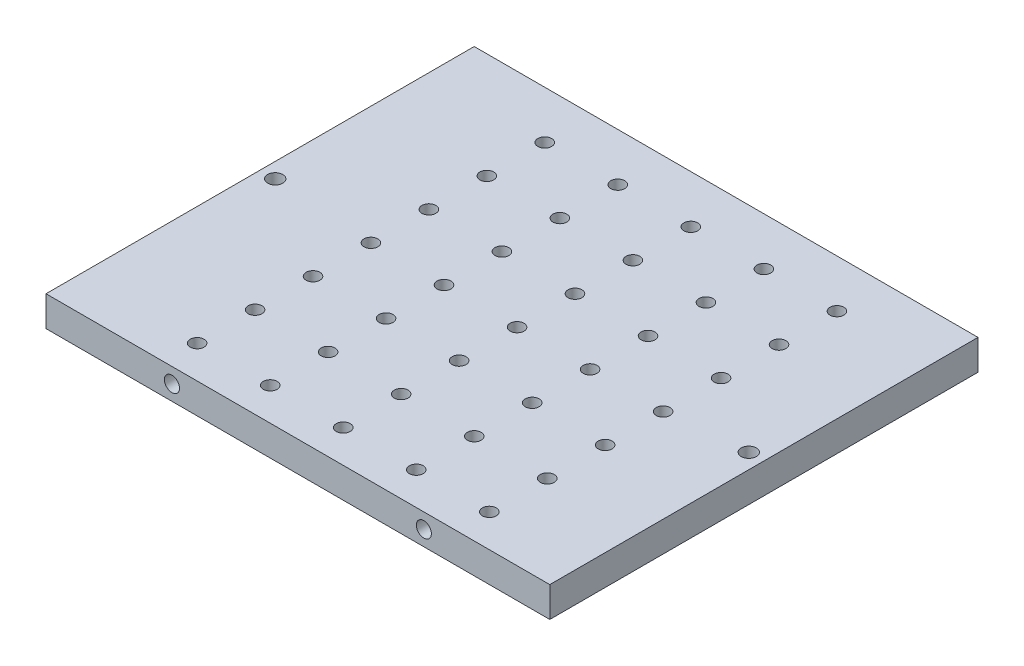
SolidWorks part; units mm, degrees
ref_plane "Plan de face" through (0, 0, 0) normal (0, 0, 1) x (1, 0, 0)
ref_plane "Plan de dessus" through (0, 0, 0) normal (0, 1, 0) x (1, 0, 0)
ref_plane "Plan de droite" through (0, 0, 0) normal (1, 0, 0) x (0, 0, -1)
sketch "Esquisse1" plane through (0, 0, 0) normal (0, 1, 0) x (1, 0, 0)
  line L1 (-50, -42.5) -> (50, -42.5)
  line L2 (-50, -42.5) -> (-50, 42.5)
  line L3 (-50, 42.5) -> (50, 42.5)
  line L4 (50, -42.5) -> (50, 42.5)
  line L5 (-50, -42.5) -> (50, 42.5) construction
  line L6 (-50, 42.5) -> (50, -42.5) construction
  point P0 (0, 0)
  dimension "D1" = 85
  dimension "D2" = 100
extrude "Boss.-Extru.1" add sketch "Esquisse1" along normal blind 6
sketch "Esquisse2" plane through (0, 0, 42.5) normal (0, 0, 1) x (1, 0, 0)
  line L0 (-50, 3) -> (29.6548, 3) construction
  line L3 (-50, 6) -> (-50, 0) construction
  line L5 (0, 0) -> (0, 17.0048) construction
  circle A0 centre (-25, 3) radius 1.5
  circle A1 centre (25, 3) radius 1.5
  dimension "D2" = 25
  dimension "D3" = 3
extrude "Enlèv. mat.-Extru.1" cut sketch "Esquisse2" against normal up to surface (85 mm away) up to face at (0, 3, -42.5)
sketch "Esquisse3" plane through (0, 0, 0) normal (0, 1, 0) x (1, 0, 0)
  line L1 (-30, 6.5) -> (35, 6.5) construction
  line L2 (-30, 6.5) -> (-30, 36.5) construction
  line L3 (-30, 36.5) -> (35, 36.5) construction
  line L4 (35, 6.5) -> (35, 36.5) construction
  line L5 (-30, 6.5) -> (35, 36.5) construction
  line L6 (-30, 36.5) -> (35, 6.5) construction
  line L7 (50, 42.5) -> (-50, 42.5) construction
  line L8 (-50, 42.5) -> (-50, -42.5) construction
  circle A0 centre (-26.5, 33) radius 1.375
  point P0 (2.5, 21.5)
  dimension "D3" = 2.75
  dimension "D4" = 3.5
  dimension "D1" = 65
  dimension "D2" = 30
  dimension "D5" = 3.5
  dimension "D6" = 6
  dimension "D7" = 20
extrude "Enlèv. mat.-Extru.2" cut sketch "Esquisse3" along normal up to surface (6 mm away) up to face at (0, 6, 0)
pattern_linear "Répétition linéaire1" count 7 spacing 11.5 along (0, 0, 1) count 5 spacing 14.5 along (1, 0, 0) of "Enlèv. mat.-Extru.2"
sketch "Esquisse4" plane through (0, 0, 0) normal (0, 1, 0) x (1, 0, 0)
  line L0 (0, 42.5) -> (0, -48.0193) construction
  line L1 (50, 42.5) -> (-50, 42.5) construction
  line L2 (-50, 0) -> (96.9461, 0) construction
  line L3 (-50, 42.5) -> (-50, -42.5) construction
  circle A0 centre (-47, 0) radius 1.5
  circle A1 centre (47, 0) radius 1.5
  dimension "D1" = 3
  dimension "D2" = 3
extrude "Enlèv. mat.-Extru.3" cut sketch "Esquisse4" along normal up to surface (6 mm away) up to face at (-26.5, 6, -22.875)
fillet "Congé1" [suppressed] radius 1
